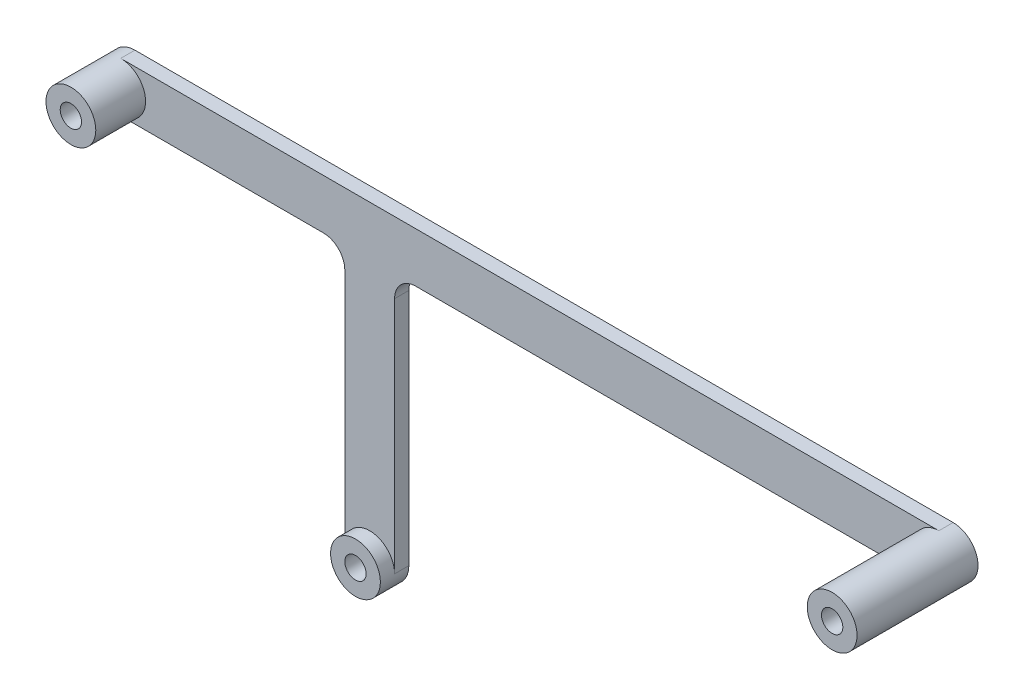
SolidWorks part; units mm, degrees
ref_plane "Front Plane" through (0, 0, 0) normal (0, 0, 1) x (1, 0, 0)
ref_plane "Top Plane" through (0, 0, 0) normal (0, 1, 0) x (1, 0, 0)
ref_plane "Right Plane" through (0, 0, 0) normal (1, 0, 0) x (0, 0, -1)
sketch "Sketch1" plane through (0, 0, 0) normal (0, 0, 1) x (1, 0, 0)
  line L0 (-35, 40) -> (80, 40) construction
  line L1 (-35, 43.5) -> (80, 43.5)
  line L2 (-35, 36.5) -> (-6.5, 36.5)
  line L3 (0, 0) -> (0, 40) construction
  line L4 (-3.5, 0) -> (-3.5, 33.5)
  line L5 (3.5, 0) -> (3.5, 33.5)
  line L6 (6.5, 36.5) -> (80, 36.5)
  circle A0 centre (-35, 40) radius 1.5
  circle A1 centre (80, 40) radius 1.5
  circle A2 centre (0, 0) radius 1.5
  arc A3 (-35, 43.5) -> (-35, 36.5) centre (-35, 40) ccw
  arc A4 (80, 36.5) -> (80, 43.5) centre (80, 40) ccw
  arc A5 (-3.5, 0) -> (3.5, 0) centre (0, 0) ccw
  arc A7 (6.5, 36.5) -> (3.5, 33.5) centre (6.5, 33.5) ccw
  arc A8 (-6.5, 36.5) -> (-3.5, 33.5) centre (-6.5, 33.5) cw
  point P7 (22.5, 40)
  point P12 (0, 20)
  point P15 (5.9305, 36.5)
  point P19 (0, 0)
  point P20 (5.9305, 36.5)
  point P21 (3.5, 36.5)
  point P22 (3.5, 36.5)
  point P23 (-3.5, 35.7748)
  point P26 (3.5, 36.5)
  dimension "Rear Hole Diameter" = 3
  dimension "Front Hole Diameter" = 3
  dimension "D7" = 3
  dimension "D8" = 2
  dimension "D9" = 2
  dimension "D10" = 3
  dimension "Rear Hole Y" = 40
  dimension "Rear Hole X" = 35
  dimension "Front Hole X" = 80
  dimension "Front Hole Y" = 40
extrude "Boss-Extrude1" add sketch "Sketch1" along normal blind 2
sketch "Sketch2" plane through (0, 0, 2) normal (0, 0, 1) x (1, 0, 0)
  circle A0 centre (-35, 40) radius 3.5
  circle A1 centre (-35, 40) radius 1.5 construction
  circle A2 centre (-35, 40) radius 1.5
  point P4 (0, 0)
extrude "Boss-Extrude2" add sketch "Sketch2" along normal blind 7
sketch "Sketch3" plane through (0, 0, 2) normal (0, 0, 1) x (1, 0, 0)
  circle A0 centre (80, 40) radius 3.5
  circle A1 centre (80, 40) radius 1.5 construction
  circle A2 centre (80, 40) radius 1.5
extrude "Boss-Extrude3" add sketch "Sketch3" along normal blind 15
sketch "Sketch4" plane through (0, 0, 2) normal (0, 0, 1) x (1, 0, 0)
  circle A1 centre (0, 0) radius 3.5
  circle A2 centre (0, 0) radius 1.5 construction
  circle A3 centre (0, 0) radius 1.5
extrude "Boss-Extrude4" add sketch "Sketch4" along normal blind 2
